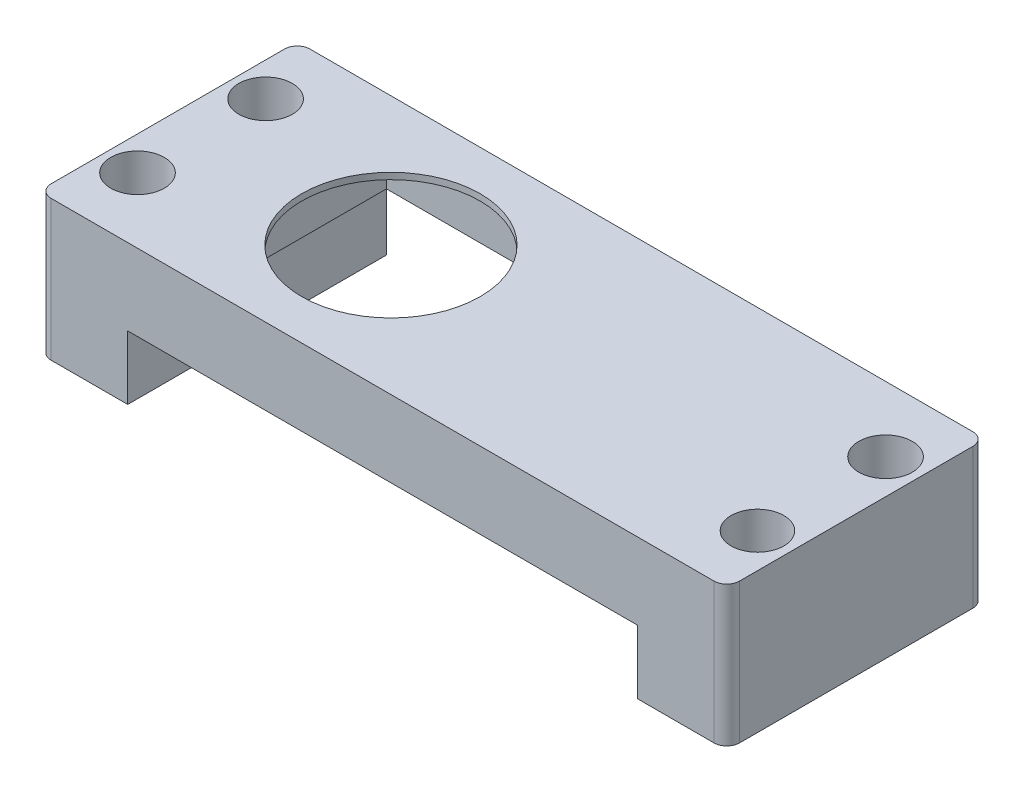
SolidWorks part; units mm, degrees
ref_plane "Front Plane" through (0, 0, 0) normal (0, 0, 1) x (1, 0, 0)
ref_plane "Top Plane" through (0, 0, 0) normal (0, 1, 0) x (1, 0, 0)
ref_plane "Right Plane" through (0, 0, 0) normal (1, 0, 0) x (0, 0, -1)
sketch "Sketch1" plane through (0, 0, 0) normal (0, 1, 0) x (1, 0, 0)
  line L1 (20, -10.15) -> (-20, -10.15)
  line L2 (20, -10.15) -> (20, 10.15)
  line L3 (20, 10.15) -> (-20, 10.15)
  line L4 (-20, -10.15) -> (-20, 10.15)
  line L5 (20, -10.15) -> (-20, 10.15) construction
  line L6 (20, 10.15) -> (-20, -10.15) construction
  point P0 (0, 0)
  dimension "D1" = 20.3
  dimension "D2" = 40
extrude "Boss-Extrude3" add sketch "Sketch1" along normal blind 6
shell "Shell1" thickness 0.5
sketch "Sketch4" plane through (0, 6, 0) normal (0, 1, 0) x (1, 0, 0)
  line L0 (20, -10.15) -> (20, 10.15) construction
  line L1 (-20, 10.15) -> (-27, 10.15)
  line L2 (-20, 10.15) -> (-20, -10.15)
  line L3 (-20, -10.15) -> (-27, -10.15)
  line L4 (-27, 10.15) -> (-27, -10.15)
  line L5 (20, -10.15) -> (27, -10.15)
  line L6 (20, -10.15) -> (20, 10.15)
  line L7 (20, 10.15) -> (27, 10.15)
  line L8 (27, -10.15) -> (27, 10.15)
  line L9 (-20, -10.15) -> (20, -10.15) construction
  line L10 (20, 10.15) -> (-20, 10.15) construction
  dimension "D1" = 7
  dimension "D2" = 7
extrude "Boss-Extrude4" add sketch "Sketch4" against normal blind 11
fillet "Fillet1" radius 1 4 edges at (27, 0.5, 10.15) (27, 0.5, -10.15) (-27, 0.5, -10.15) (-27, 0.5, 10.15)
sketch "Sketch5" plane through (0, -5, 0) normal (0, -1, 0) x (1, 0, 0)
  line L0 (0, 0) -> (-26.2894, 0) construction
  line L1 (-26.2894, 0) -> (30.9893, 0) construction
  line L2 (-24.3575, -12.4659) -> (-24.3575, 18.6718) construction
  line L3 (24.2842, 17.0412) -> (24.2842, -13.8861) construction
  line L4 (0, 0) -> (0, 15.3306) construction
  line L8 (-30.9705, 5.025) -> (30.9893, 5.025) construction
  line L9 (30.9893, -5.025) -> (-24.0302, -5.025) construction
  line L10 (20, -10.15) -> (-20, -10.15) construction
  circle A0 centre (-24.3575, 5.025) radius 2.1
  circle A1 centre (-24.3575, -5.025) radius 2.1
  circle A2 centre (24.2842, 5.025) radius 2.0701
  circle A3 centre (24.2842, -5.025) radius 2.1
  dimension "D3" = 4.2
  dimension "D4" = 4.2
  dimension "D1" = 4.125
  dimension "D2" = 4.125
extrude "Cut-Extrude3" cut sketch "Sketch5" against normal blind 6
sketch "Sketch7" plane through (0, 5.5, 0) normal (0, -1, 0) x (1, 0, 0)
  line L0 (-19.5, -9.65) -> (-19.5, 9.65) construction
  circle A0 centre (-9.5, 0) radius 7
  dimension "D1" = 14
  dimension "D2" = 10
extrude "Cut-Extrude4" cut sketch "Sketch7" against normal blind 88
sketch "Sketch8" plane through (0, 1, 0) normal (0, -1, 0) x (1, 0, 0)
  circle A0 centre (24.2842, -5.025) radius 2.1 construction
  circle A1 centre (24.2842, 5.025) radius 2.0701 construction
  circle A2 centre (-24.3575, 5.025) radius 2.1 construction
  circle A3 centre (-24.3575, -5.025) radius 2.1 construction
  circle A4 centre (24.2842, -5.025) radius 2.1
  circle A5 centre (24.2842, 5.025) radius 2.0701
  circle A6 centre (-24.3575, 5.025) radius 2.1
  circle A7 centre (-24.3575, -5.025) radius 2.1
extrude "Cut-Extrude5" cut sketch "Sketch8" against normal through all both and the other way through all
